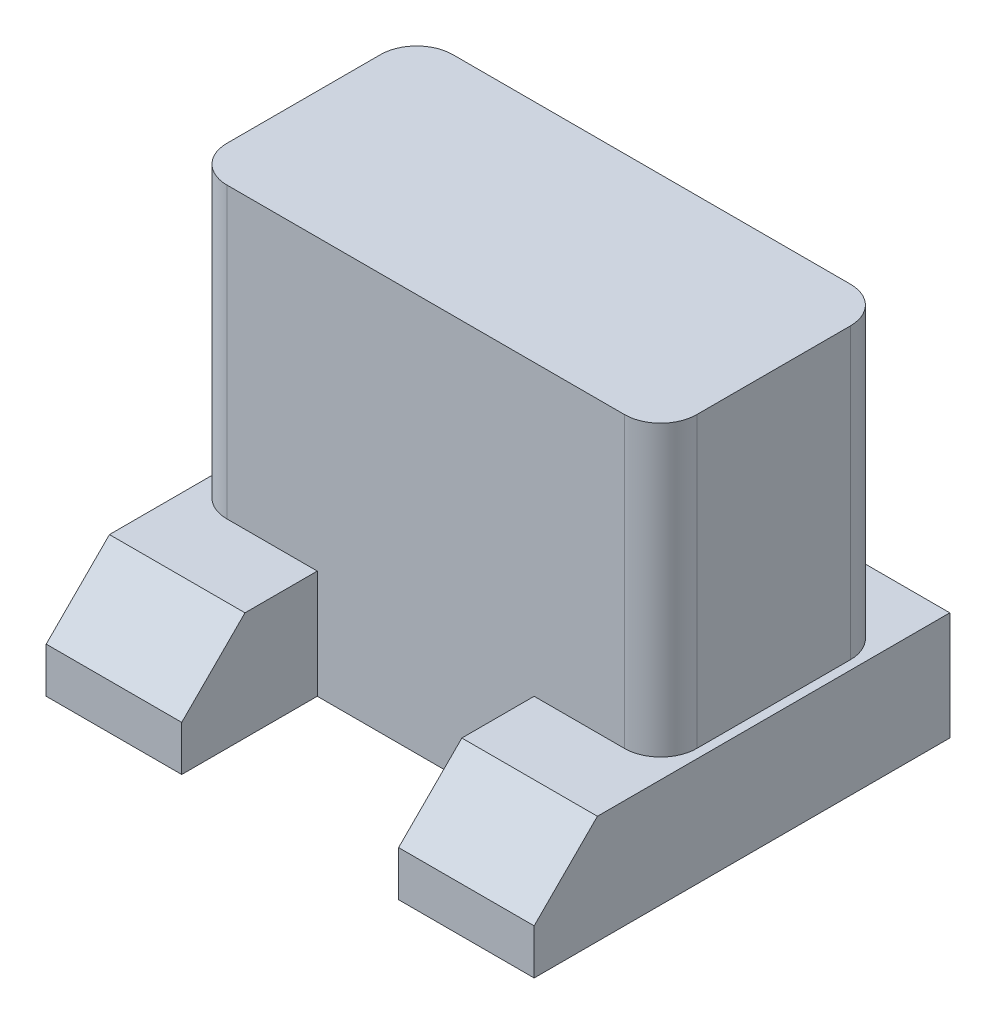
SolidWorks part; units mm, degrees
ref_plane "前视基准面" through (0, 0, 0) normal (0, 0, 1) x (1, 0, 0)
ref_plane "上视基准面" through (0, 0, 0) normal (0, 1, 0) x (1, 0, 0)
ref_plane "右视基准面" through (0, 0, 0) normal (1, 0, 0) x (0, 0, -1)
sketch "草图1" plane through (0, 0, 0) normal (0, 1, 0) x (1, 0, 0)
  line L0 (-2.6, 0.85) -> (-2.6, -0.85)
  line L1 (-2.2, 1.35) -> (2.2, 1.35)
  line L2 (-2.7, 0.85) -> (-2.7, -0.85)
  line L3 (-2.2, -1.35) -> (2.2, -1.35)
  line L4 (2.7, 0.85) -> (2.7, -0.85)
  line L5 (-2.7, 1.35) -> (2.7, -1.35) construction
  line L6 (-2.7, -1.35) -> (2.7, 1.35) construction
  line L7 (-2.2, -1.25) -> (2.2, -1.25)
  line L8 (2.6, 0.85) -> (2.6, -0.85)
  line L9 (-2.2, 1.25) -> (2.2, 1.25)
  arc A0 (2.2, 1.35) -> (2.7, 0.85) centre (2.2, 0.85) cw
  arc A1 (2.2, -1.35) -> (2.7, -0.85) centre (2.2, -0.85) ccw
  arc A2 (-2.7, -0.85) -> (-2.2, -1.35) centre (-2.2, -0.85) ccw
  arc A3 (-2.2, 1.35) -> (-2.7, 0.85) centre (-2.2, 0.85) ccw
  arc A4 (-2.2, 1.25) -> (-2.6, 0.85) centre (-2.2, 0.85) ccw
  arc A5 (-2.6, -0.85) -> (-2.2, -1.25) centre (-2.2, -0.85) ccw
  arc A6 (2.2, -1.25) -> (2.6, -0.85) centre (2.2, -0.85) ccw
  arc A7 (2.2, 1.25) -> (2.6, 0.85) centre (2.2, 0.85) cw
  point P0 (0, 0)
  dimension "D3" = 0.5
  dimension "D1" = 5.4
  dimension "D2" = 2.7
  dimension "D4" = 0.1
extrude "凸台-拉伸3" add sketch "草图1" along normal blind 3.2 and the other way blind 1.2 contours A4 L0 A5 L7 A6 L8 A7 L9
sketch "草图2" plane through (0, 0, 0) normal (0, 1, 0) x (1, 0, 0)
  line L1 (-2.7, 1.25) -> (2.7, 1.25)
  line L2 (-2.7, 1.25) -> (-2.7, -1.25)
  line L3 (-2.7, -1.25) -> (2.7, -1.25)
  line L4 (2.7, 1.25) -> (2.7, -1.25)
  line L5 (-2.7, 1.25) -> (2.7, -1.25) construction
  line L6 (-2.7, -1.25) -> (2.7, 1.25) construction
  point P0 (0, 0)
  dimension "D1" = 5.4
  dimension "D2" = 2.5
extrude "凸台-拉伸4" add sketch "草图2" against normal blind 1.2
ref_plane "基准面4" through (0, 0, -1.25) normal (0, 0, -1) x (-1, 0, 0)
ref_plane "基准面5" through (0, 0, 1.25) normal (0, 0, 1) x (1, 0, 0)
ref_plane "基准面6" through (0, -1.2, 0) normal (0, -1, 0) x (-1, 0, 0)
sketch "草图5" plane through (0, -1.2, 0) normal (0, -1, 0) x (-1, 0, 0)
  line L1 (2, 0.9) -> (-2, 0.9)
  line L2 (2, 0.9) -> (2, -0.6)
  line L3 (2, -0.6) -> (-2, -0.6)
  line L4 (-2, 0.9) -> (-2, -0.6)
  point P6 (0, -0.6)
  dimension "D1" = 4
  dimension "D2" = 1.5
extrude "凸台-拉伸7" add sketch "草图5" along normal blind 0.5
sketch "草图6" plane through (0, 0, -1.25) normal (0, 0, -1) x (-1, 0, 0)
  line L0 (-2, -1.2) -> (2, -1.2) construction
  line L1 (2.7, 0) -> (1.2, 0)
  line L2 (2.7, 0) -> (2.7, -1.2)
  line L3 (2.7, -1.2) -> (1.2, -1.2)
  line L4 (1.2, 0) -> (1.2, -1.2)
  line L5 (2.7, -1.2) -> (-2.7, -1.2) construction
  line L6 (-2.7, 0) -> (-1.2, 0)
  line L7 (-2.7, 0) -> (-2.7, -1.2)
  line L8 (-2.7, -1.2) -> (-1.2, -1.2)
  line L9 (-1.2, 0) -> (-1.2, -1.2)
  dimension "D1" = 2.4
extrude "凸台-拉伸8" add sketch "草图6" along normal blind 0.6
sketch "草图7" plane through (0, 0, 1.25) normal (0, 0, 1) x (1, 0, 0)
  line L4 (2.7, 0) -> (1.2, 0)
  line L5 (1.2, 0) -> (1.2, -1.2)
  line L6 (1.2, -1.2) -> (2.7, -1.2)
  line L7 (2.7, -1.2) -> (2.7, 0)
  line L8 (2.7, 0) -> (1.2, 0)
  line L9 (1.2, 0) -> (1.2, -1.2)
  line L10 (1.2, -1.2) -> (2.7, -1.2)
  line L11 (2.7, -1.2) -> (2.7, 0)
  line L12 (-1.2, 0) -> (-2.7, 0)
  line L13 (-1.2, -1.2) -> (-1.2, 0)
  line L14 (-2.7, -1.2) -> (-1.2, -1.2)
  line L15 (-2.7, 0) -> (-2.7, -1.2)
  line L16 (-1.2, 0) -> (-2.7, 0)
  line L17 (-1.2, -1.2) -> (-1.2, 0)
  line L18 (-2.7, -1.2) -> (-1.2, -1.2)
  line L19 (-2.7, 0) -> (-2.7, -1.2)
  dimension "D1" = 0
  dimension "D2" = 0
extrude "凸台-拉伸9" add sketch "草图7" along normal blind 1.5
chamfer "倒角2" distance 0.7 angle 45 2 edges at (-1.95, 0, 2.75) (1.95, 0, 2.75)
